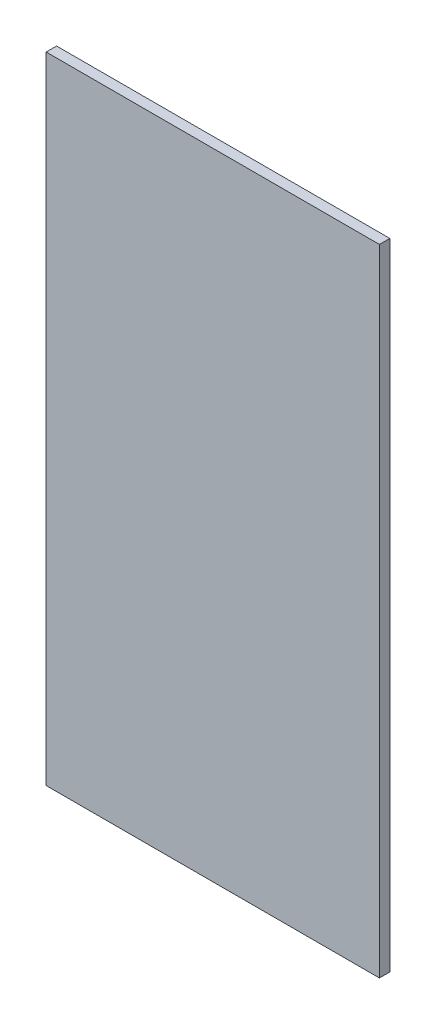
SolidWorks part; units mm, degrees
ref_plane "Front Plane" through (0, 0, 0) normal (0, 0, 1) x (1, 0, 0)
ref_plane "Top Plane" through (0, 0, 0) normal (0, 1, 0) x (1, 0, 0)
ref_plane "Right Plane" through (0, 0, 0) normal (1, 0, 0) x (0, 0, -1)
sketch "Sketch1" plane through (0, 0, 0) normal (0, 0, 1) x (1, 0, 0)
  line L1 (-63.1523, 281.8234) -> (140.0477, 281.8234)
  line L2 (-63.1523, 281.8234) -> (-63.1523, -105.5266)
  line L3 (-63.1523, -105.5266) -> (140.0477, -105.5266)
  line L4 (140.0477, 281.8234) -> (140.0477, -105.5266)
  dimension "D1" = 203.2
  dimension "D2" = 387.35
extrude "Boss-Extrude1" add sketch "Sketch1" along normal blind 6.35
